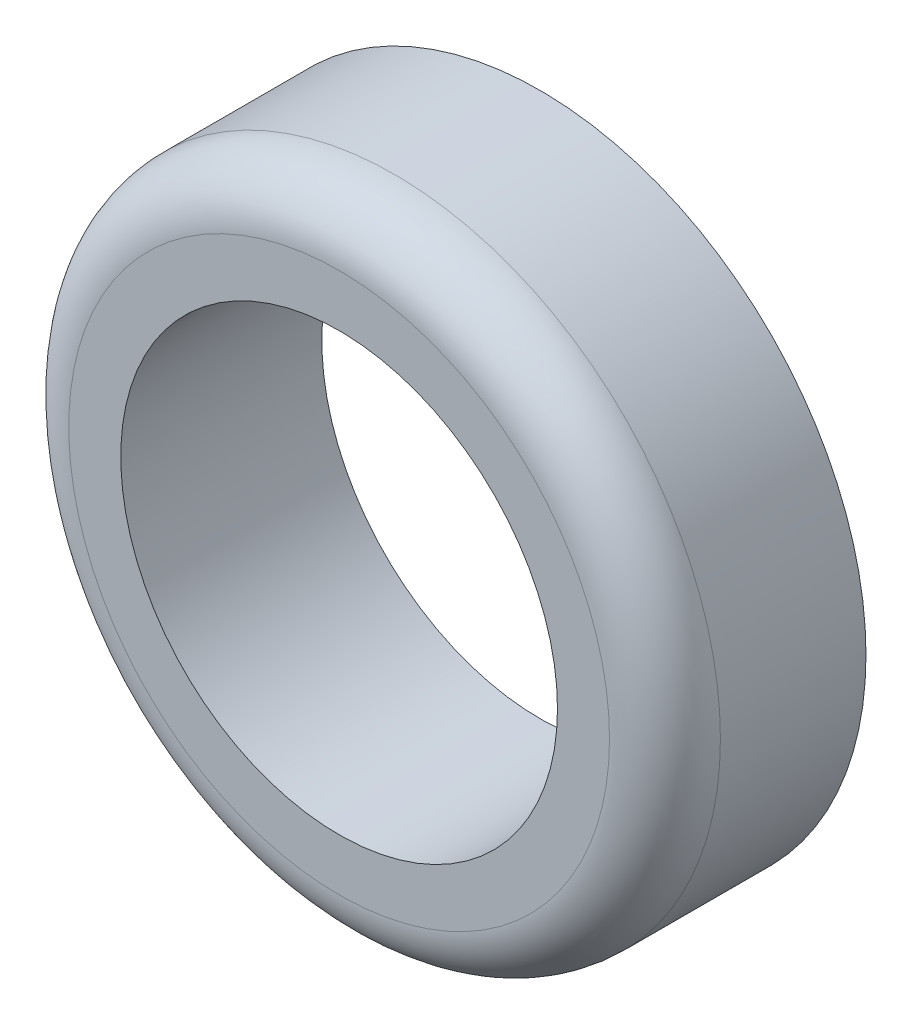
SolidWorks part; units mm, degrees
ref_plane "Front Plane" through (0, 0, 0) normal (0, 0, 1) x (1, 0, 0)
ref_plane "Top Plane" through (0, 0, 0) normal (0, 1, 0) x (1, 0, 0)
ref_plane "Right Plane" through (0, 0, 0) normal (1, 0, 0) x (0, 0, -1)
sketch "Sketch1" plane through (0, 0, 0) normal (0, 0, 1) x (1, 0, 0)
  circle A0 centre (0, 0) radius 47.005 construction
  circle A1 centre (0, 0) radius 47.005
  circle A2 centre (0, 0) radius 31.5 construction
  circle A3 centre (0, 0) radius 31.5
extrude "Boss-Extrude1" add sketch "Sketch1" along normal blind 29
fillet "Fillet1" radius 8 1 edges at (47.005, 0, 29)
